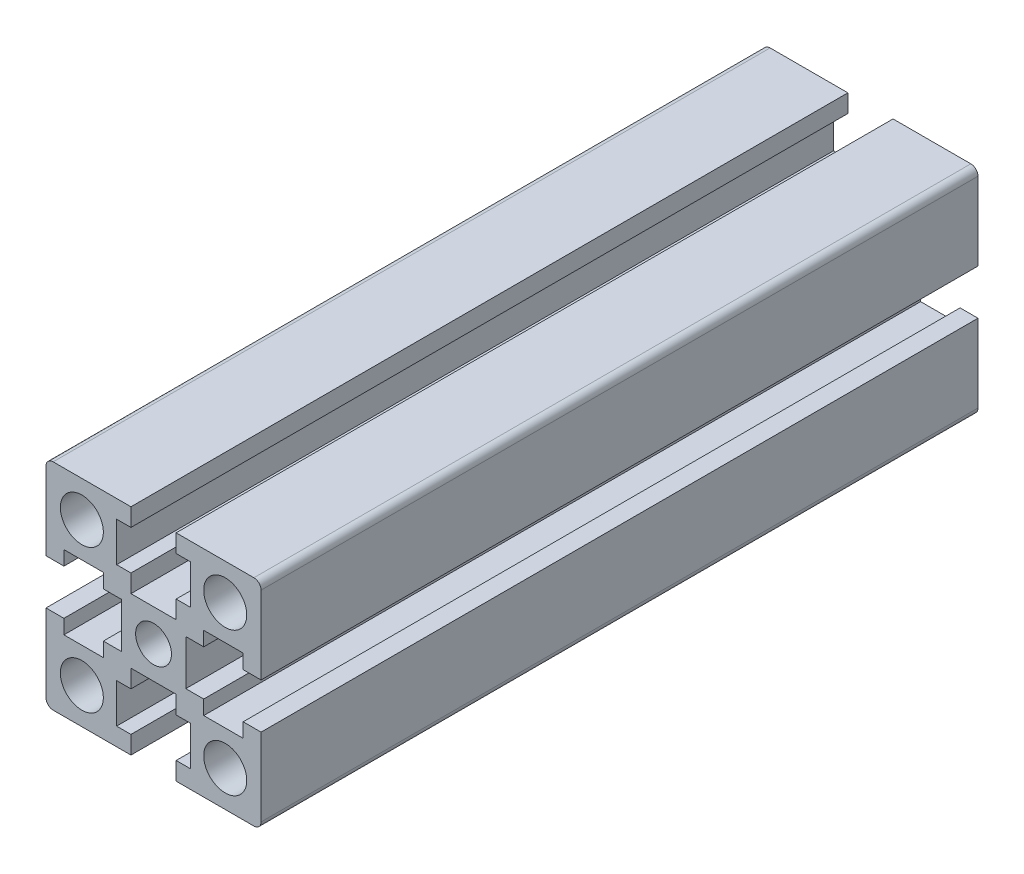
SolidWorks part; units mm, degrees
ref_plane "前视基准面" through (0, 0, 0) normal (0, 0, 1) x (1, 0, 0)
ref_plane "上视基准面" through (0, 0, 0) normal (0, 1, 0) x (1, 0, 0)
ref_plane "右视基准面" through (0, 0, 0) normal (1, 0, 0) x (0, 0, -1)
sketch "草图1" plane through (0, 0, 0) normal (0, 0, 1) x (1, 0, 0)
  line B0 (-11.4365, -15.1172) -> (-11.4365, -4.2672)
  line B1 (-11.4365, 2.0328) -> (-11.4365, 12.8828)
  line B2 (18.5635, -15.1172) -> (18.5635, -4.2672)
  line B3 (18.5635, 2.0328) -> (18.5635, 12.8828)
  line B4 (-10.4365, -16.1172) -> (0.4135, -16.1172)
  line B5 (6.7135, -16.1172) -> (17.5635, -16.1172)
  line B6 (0.4135, -5.6172) -> (6.7135, -5.6172)
  line B7 (-1.5865, -8.1172) -> (0.4135, -8.1172)
  line B8 (6.7135, -8.1172) -> (8.7135, -8.1172)
  line B9 (-1.5865, -13.6172) -> (0.4135, -13.6172)
  line B10 (6.7135, -13.6172) -> (8.7135, -13.6172)
  line B11 (17.5635, 13.8828) -> (6.7135, 13.8828)
  line B12 (0.4135, 13.8828) -> (-10.4365, 13.8828)
  line B13 (6.7135, -13.6172) -> (6.7135, -16.1172)
  line B14 (0.4135, -13.6172) -> (0.4135, -16.1172)
  line B15 (8.7135, -13.6172) -> (8.7135, -8.1172)
  line B16 (-1.5865, -13.6172) -> (-1.5865, -8.1172)
  line B17 (0.4135, -5.6172) -> (0.4135, -8.1172)
  line B18 (6.7135, -5.6172) -> (6.7135, -8.1172)
  line B19 (8.0635, -4.2672) -> (8.0635, 2.0328)
  line B20 (10.5635, -6.2672) -> (10.5635, -4.2672)
  line B21 (10.5635, 2.0328) -> (10.5635, 4.0328)
  line B22 (16.0635, -6.2672) -> (16.0635, -4.2672)
  line B23 (16.0635, 2.0328) -> (16.0635, 4.0328)
  line B24 (16.0635, 2.0328) -> (18.5635, 2.0328)
  line B25 (16.0635, -4.2672) -> (18.5635, -4.2672)
  line B26 (16.0635, 4.0328) -> (10.5635, 4.0328)
  line B27 (16.0635, -6.2672) -> (10.5635, -6.2672)
  line B28 (8.0635, -4.2672) -> (10.5635, -4.2672)
  line B29 (8.0635, 2.0328) -> (10.5635, 2.0328)
  line B30 (6.7135, 3.3828) -> (0.4135, 3.3828)
  line B31 (8.7135, 5.8828) -> (6.7135, 5.8828)
  line B32 (0.4135, 5.8828) -> (-1.5865, 5.8828)
  line B33 (8.7135, 11.3828) -> (6.7135, 11.3828)
  line B34 (0.4135, 11.3828) -> (-1.5865, 11.3828)
  line B35 (0.4135, 11.3828) -> (0.4135, 13.8828)
  line B36 (6.7135, 11.3828) -> (6.7135, 13.8828)
  line B37 (-1.5865, 11.3828) -> (-1.5865, 5.8828)
  line B38 (8.7135, 11.3828) -> (8.7135, 5.8828)
  line B39 (6.7135, 3.3828) -> (6.7135, 5.8828)
  line B40 (0.4135, 3.3828) -> (0.4135, 5.8828)
  line B41 (-0.9365, 2.0328) -> (-0.9365, -4.2672)
  line B42 (-3.4365, 4.0328) -> (-3.4365, 2.0328)
  line B43 (-3.4365, -4.2672) -> (-3.4365, -6.2672)
  line B44 (-8.9365, 4.0328) -> (-8.9365, 2.0328)
  line B45 (-8.9365, -4.2672) -> (-8.9365, -6.2672)
  line B46 (-8.9365, -4.2672) -> (-11.4365, -4.2672)
  line B47 (-8.9365, 2.0328) -> (-11.4365, 2.0328)
  line B48 (-8.9365, -6.2672) -> (-3.4365, -6.2672)
  line B49 (-8.9365, 4.0328) -> (-3.4365, 4.0328)
  line B50 (-0.9365, 2.0328) -> (-3.4365, 2.0328)
  line B51 (-0.9365, -4.2672) -> (-3.4365, -4.2672)
  arc B52 (18.5635, 12.8828) -> (17.5635, 13.8828) centre (17.5635, 12.8828) ccw
  arc B53 (-11.4365, -15.1172) -> (-10.4365, -16.1172) centre (-10.4365, -15.1172) ccw
  arc B54 (17.5635, -16.1172) -> (18.5635, -15.1172) centre (17.5635, -15.1172) ccw
  arc B55 (-10.4365, 13.8828) -> (-11.4365, 12.8828) centre (-10.4365, 12.8828) ccw
  circle B56 centre (-6.4365, 8.8828) radius 3
  circle B57 centre (-6.4365, -11.1172) radius 3
  circle B58 centre (13.5635, -11.1172) radius 3
  circle B59 centre (13.5635, 8.8828) radius 3
  circle B60 centre (3.5635, -1.1172) radius 2.5
sketch_block_instance "A$C03D85FBF-1"
sketch_block "A$C03D85FBF"
extrude "凸台-拉伸1" add sketch "草图1" along normal blind 100
